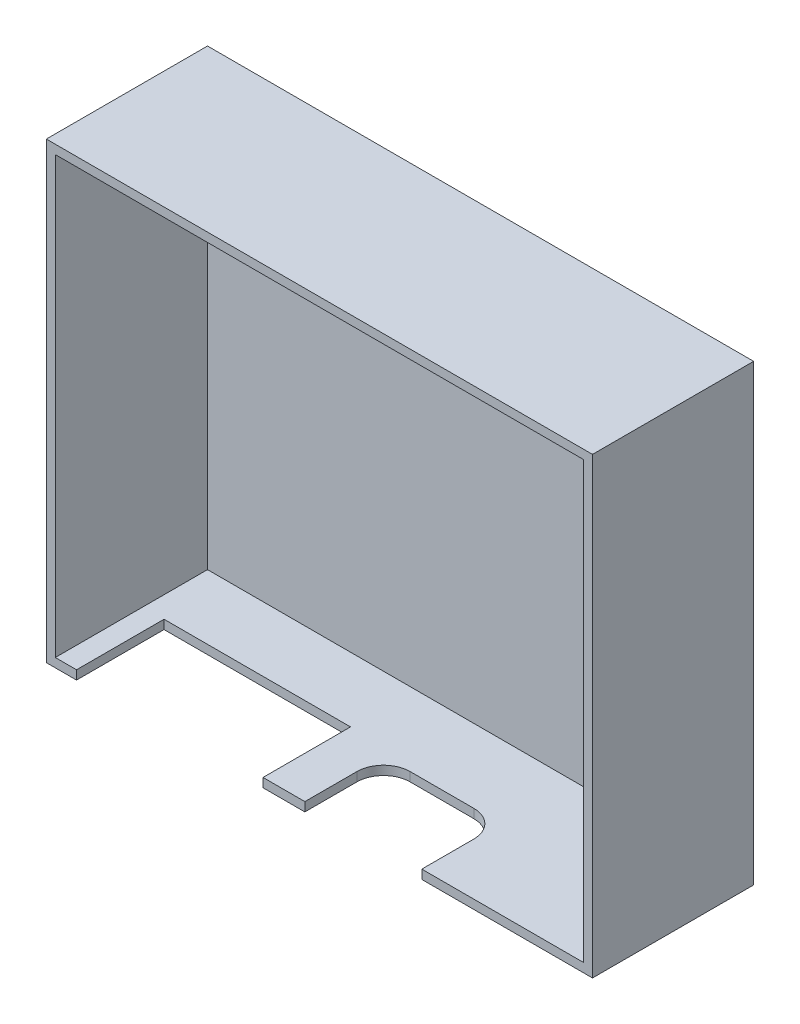
SolidWorks part; units mm, degrees
ref_plane "Front Plane" through (0, 0, 0) normal (0, 0, 1) x (1, 0, 0)
ref_plane "Top Plane" through (0, 0, 0) normal (0, 1, 0) x (1, 0, 0)
ref_plane "Right Plane" through (0, 0, 0) normal (1, 0, 0) x (0, 0, -1)
sketch "Sketch1" plane through (0, 0, 0) normal (0, 0, 1) x (1, 0, 0)
  line L0 (73.5, -129.8) -> (73.5, -36.5) construction
  line L1 (68.5, -31.5) -> (190.5, -31.5)
  line L2 (68.5, -31.5) -> (68.5, -132.8)
  line L3 (68.5, -132.8) -> (190.5, -132.8)
  line L4 (190.5, -31.5) -> (190.5, -132.8)
  line L5 (73.5, -36.5) -> (185.5, -36.5) construction
  line L6 (185.5, -36.5) -> (185.5, -129.8) construction
  line L7 (185.5, -129.8) -> (73.5, -129.8) construction
  dimension "D1" = 5
  dimension "D2" = 5
  dimension "D3" = 5
  dimension "D4" = 3
extrude "Boss-Extrude1" add sketch "Sketch1" along normal mid plane 36
sketch "Sketch2" plane through (0, 0, 18) normal (0, 0, 1) x (1, 0, 0)
  line L12 (70.5, -33.5) -> (70.5, -130.8)
  line L13 (70.5, -130.8) -> (188.5, -130.8)
  line L14 (188.5, -130.8) -> (188.5, -33.5)
  line L15 (188.5, -33.5) -> (70.5, -33.5)
  line L16 (70.5, -33.5) -> (70.5, -130.8)
  line L17 (70.5, -130.8) -> (188.5, -130.8)
  line L18 (188.5, -130.8) -> (188.5, -33.5)
  line L19 (188.5, -33.5) -> (70.5, -33.5)
  dimension "D1" = 2
extrude "Cut-Extrude1" cut sketch "Sketch2" against normal blind 34
sketch "Sketch4" plane through (0, -132.8, 0) normal (0, -1, 0) x (-1, 0, 0)
  circle A0 centre (-132.2, -6.385) radius 5.9535
  circle A1 centre (-146.4145, -6.385) radius 5.9535
extrude "Cut-Extrude5" cut sketch "Sketch4" against normal blind 2
sketch "Sketch5" plane through (0, -132.8, 0) normal (0, -1, 0) x (-1, 0, 0)
  line L0 (-68.5, -18) -> (-190.5, -18) construction
  line L1 (-75.2413, -18) -> (-116.8999, -18)
  line L2 (-75.2413, -18) -> (-75.2413, 1.5508)
  line L3 (-75.2413, 1.5508) -> (-116.8999, 1.5508)
  line L4 (-116.8999, -18) -> (-116.8999, 1.5508)
extrude "Cut-Extrude10" cut sketch "Sketch5" against normal blind 2
sketch "Sketch9" plane through (0, -132.8, 0) normal (0, -1, 0) x (-1, 0, 0)
  line L0 (-68.5, -18) -> (-75.2413, -18) construction
  line L1 (-140.461, -18) -> (-152.3681, -18)
  line L2 (-140.461, -18) -> (-140.461, -6.385)
  line L3 (-140.461, -6.385) -> (-152.3681, -6.385)
  line L4 (-152.3681, -18) -> (-152.3681, -6.385)
  circle A0 centre (-146.4145, -6.385) radius 5.9535 construction
extrude "Cut-Extrude12" cut sketch "Sketch9" against normal blind 5
sketch "Sketch10" plane through (0, -132.8, 0) normal (0, -1, 0) x (-1, 0, 0)
  line L0 (-68.5, -18) -> (-75.2413, -18) construction
  line L1 (-126.2465, -6.385) -> (-138.1535, -6.385)
  line L2 (-126.2465, -6.385) -> (-126.2465, -18)
  line L3 (-126.2465, -18) -> (-138.1535, -18)
  line L4 (-138.1535, -6.385) -> (-138.1535, -18)
  circle A0 centre (-132.2, -6.385) radius 5.9535 construction
extrude "Cut-Extrude13" cut sketch "Sketch10" against normal blind 5
sketch "Sketch11" plane through (0, 0, -16) normal (0, 0, 1) x (1, 0, 0)
  circle A4 centre (91.5, -40.5) radius 1.25
  dimension "D1" = 2.5
extrude "Boss-Extrude6" add sketch "Sketch11" along normal blind 17
sketch "Sketch14" plane through (0, 0, -16) normal (0, 0, 1) x (1, 0, 0)
  circle A0 centre (166.43, -40.5) radius 1.25
  dimension "D1" = 2.5
extrude "Boss-Extrude8" add sketch "Sketch14" along normal blind 17 contours A0
sketch "Sketch15" plane through (0, 0, -16) normal (0, 0, 1) x (1, 0, 0)
  circle A1 centre (180.9, -126.3) radius 1.25
  dimension "D1" = 2.5
extrude "Boss-Extrude10" add sketch "Sketch15" along normal blind 17 contours A1
sketch "Sketch16" plane through (0, -132.8, 0) normal (0, -1, 0) x (-1, 0, 0)
  line L0 (-188.5, -18) -> (-70.5, -18) construction
  line L1 (-146.4145, -0.4315) -> (-132.2, -0.4315)
  line L2 (-146.4145, -0.4315) -> (-146.4145, -18)
  line L3 (-146.4145, -18) -> (-132.2, -18)
  line L4 (-132.2, -0.4315) -> (-132.2, -18)
  arc A0 (-140.461, -6.385) -> (-152.3681, -6.385) centre (-146.4145, -6.385) ccw construction
extrude "Cut-Extrude14" cut sketch "Sketch16" against normal blind 5
sketch "Sketch17" plane through (0, 0, -16) normal (0, 0, 1) x (1, 0, 0)
  circle A0 centre (91.5, -40.5) radius 1.6
extrude "Boss-Extrude11" add sketch "Sketch17" along normal blind 1 draft 20
sketch "Sketch18" plane through (0, 0, -16) normal (0, 0, 1) x (1, 0, 0)
  circle A0 centre (166.43, -40.5) radius 1.6
extrude "Boss-Extrude13" add sketch "Sketch18" along normal blind 1 draft 20
sketch "Sketch19" plane through (0, 0, -16) normal (0, 0, 1) x (1, 0, 0)
  circle A0 centre (180.9, -126.3) radius 1.5133
extrude "Boss-Extrude14" add sketch "Sketch19" along normal blind 1 draft 20
